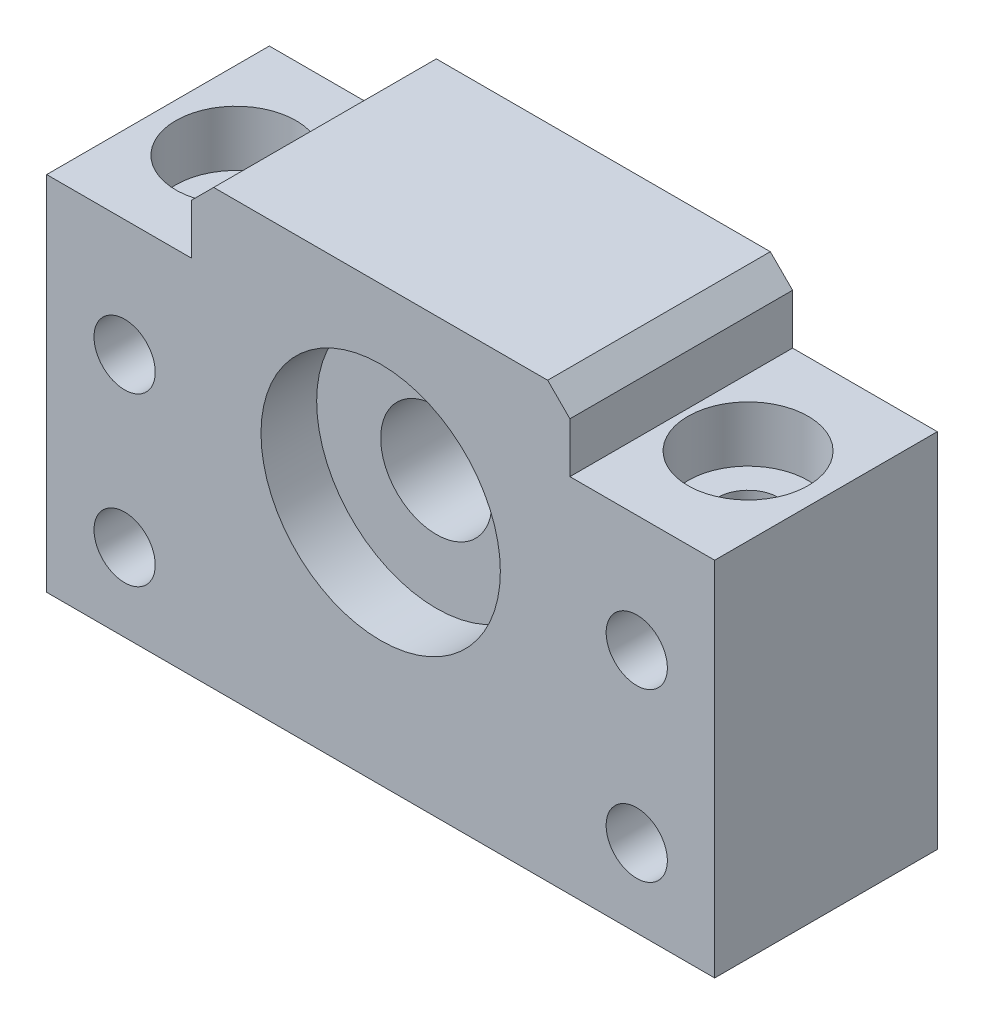
SolidWorks part; units mm, degrees
ref_plane "Front Plane" through (0, 0, 0) normal (0, 0, 1) x (1, 0, 0)
ref_plane "Top Plane" through (0, 0, 0) normal (0, 1, 0) x (1, 0, 0)
ref_plane "Right Plane" through (0, 0, 0) normal (1, 0, 0) x (0, 0, -1)
sketch "Sketch2" plane through (0, 0, 0) normal (0, 0, 1) x (1, 0, 0)
  line L0 (15, 17) -> (-15, 17)
  line L1 (-15, 17) -> (-17, 15)
  line L2 (-17, 15) -> (-17, 10.5)
  line L3 (-17, 15) -> (-17, 17) construction
  line L4 (-17, 10.5) -> (-30, 10.5)
  line L5 (-30, 10.5) -> (-30, -22)
  line L6 (-30, -22) -> (30, -22)
  line L7 (0, 17) -> (0, -22) construction
  line L8 (-23, 0) -> (-23, -15) construction
  line L9 (23, -15) -> (-23, -15) construction
  line L10 (0, 0) -> (-23, 0) construction
  line L11 (30, 10.5) -> (30, -22)
  line L12 (17, 10.5) -> (30, 10.5)
  line L13 (17, 15) -> (17, 10.5)
  line L14 (15, 17) -> (17, 15)
  line L15 (-17, 17) -> (-15, 17) construction
  circle A1 centre (0, 0) radius 10.75
  circle A2 centre (-23, 0) radius 2.75
  circle A3 centre (-23, -15) radius 2.75
  circle A4 centre (23, -15) radius 2.75
  circle A5 centre (23, 0) radius 2.75
  point P1 (0, 0)
  point P24 (0, -15)
  dimension "D3" = 5.5
  dimension "D7" = 21.5
  dimension "D1" = 32.5
  dimension "D2" = 39
  dimension "D4" = 60
  dimension "D5" = 46
  dimension "D6" = 15
  dimension "D8" = 34
  dimension "D9" = 2
  dimension "D10" = 7
extrude "Boss-Extrude2" add sketch "Sketch2" along normal mid plane 20
sketch "Sketch3" plane through (0, -22, 0) normal (0, -1, 0) x (1, 0, 0)
  line L0 (0, -10) -> (0, 10) construction
  line L3 (-23, 0) -> (23, 0) construction
  line L5 (25.75, 0) -> (25.75, -10) construction
  line L6 (-30, -10) -> (30, -10) construction
  line L7 (-30, 10) -> (30, 10) construction
  line L9 (20.25, 0) -> (20.25, -10) construction
  circle A0 centre (23, 0) radius 2.75
  circle A2 centre (-23, 0) radius 2.75
  point P5 (0, 0)
  point P15 (0, 0)
  point P17 (0, -6.1725)
extrude "Cut-Extrude1" cut sketch "Sketch3" against normal through all
sketch "Sketch4" plane through (0, 10.5, 0) normal (0, 1, 0) x (1, 0, 0)
  circle A0 centre (-23, 0) radius 5.4
  circle A3 centre (23, 0) radius 5.4
  dimension "D1" = 10.8
extrude "Cut-Extrude2" cut sketch "Sketch4" against normal blind 5
sketch "Sketch5" plane through (0, 0, 0) normal (0, 0, 1) x (1, 0, 0)
  circle A0 centre (0, 0) radius 5
  circle A1 centre (0, 0) radius 10.75
  circle A2 centre (0, 0) radius 10.75 construction
  dimension "D1" = 10
extrude "Boss-Extrude4" add sketch "Sketch5" along normal mid plane 10 separate body
